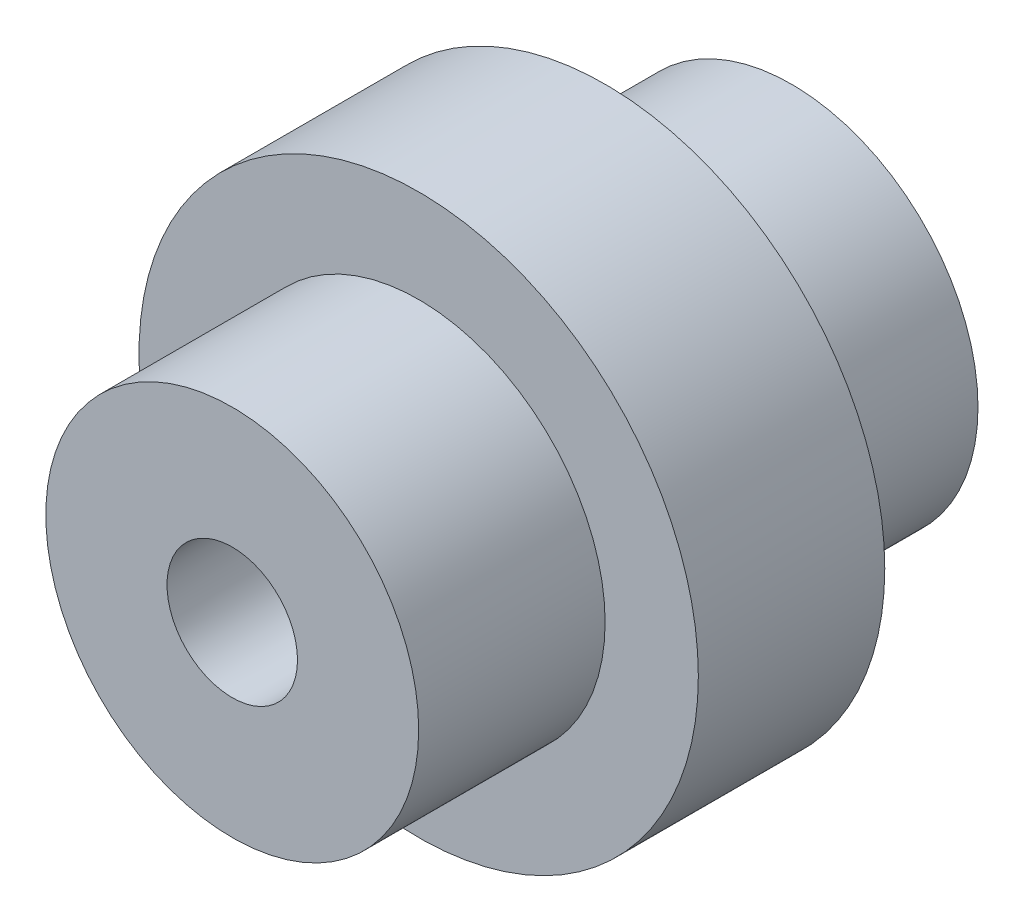
SolidWorks part; units mm, degrees
ref_plane "Front Plane" through (0, 0, 0) normal (0, 0, 1) x (1, 0, 0)
ref_plane "Top Plane" through (0, 0, 0) normal (0, 1, 0) x (1, 0, 0)
ref_plane "Right Plane" through (0, 0, 0) normal (1, 0, 0) x (0, 0, -1)
ref_plane "Plane4" through (0, 0, 33) normal (0, 0, 1) x (1, 0, 0)
sketch "Sketch1" plane through (0, 0, 33) normal (0, 0, 1) x (1, 0, 0)
  circle A0 centre (0, 0) radius 6
extrude "Boss-Extrude1" add sketch "Sketch1" against normal blind 4
sketch "Sketch2" plane through (0, 0, 33) normal (0, 0, 1) x (1, 0, 0)
  circle A0 centre (0, 0) radius 4
extrude "Boss-Extrude2" add sketch "Sketch2" along normal blind 4 and the other way blind 8
sketch "Sketch3" plane through (0, 0, 33) normal (0, 0, 1) x (1, 0, 0)
  circle A0 centre (0, 0) radius 2
ref_plane "Plane5" through (0, 0, 25) normal (0, 0, 1) x (1, 0, 0)
sketch "Sketch6" plane through (0, 0, 25) normal (0, 0, 1) x (1, 0, 0)
  circle A0 centre (0, 0) radius 1.46
ref_plane "Plane6" through (0, 0, 37) normal (0, 0, 1) x (1, 0, 0)
sketch "Sketch8" plane through (0, 0, 37) normal (0, 0, 1) x (1, 0, 0)
  circle A0 centre (0, 0) radius 1.4
loft "Cut-Loft2" cut profiles "Sketch8", "Sketch6"
